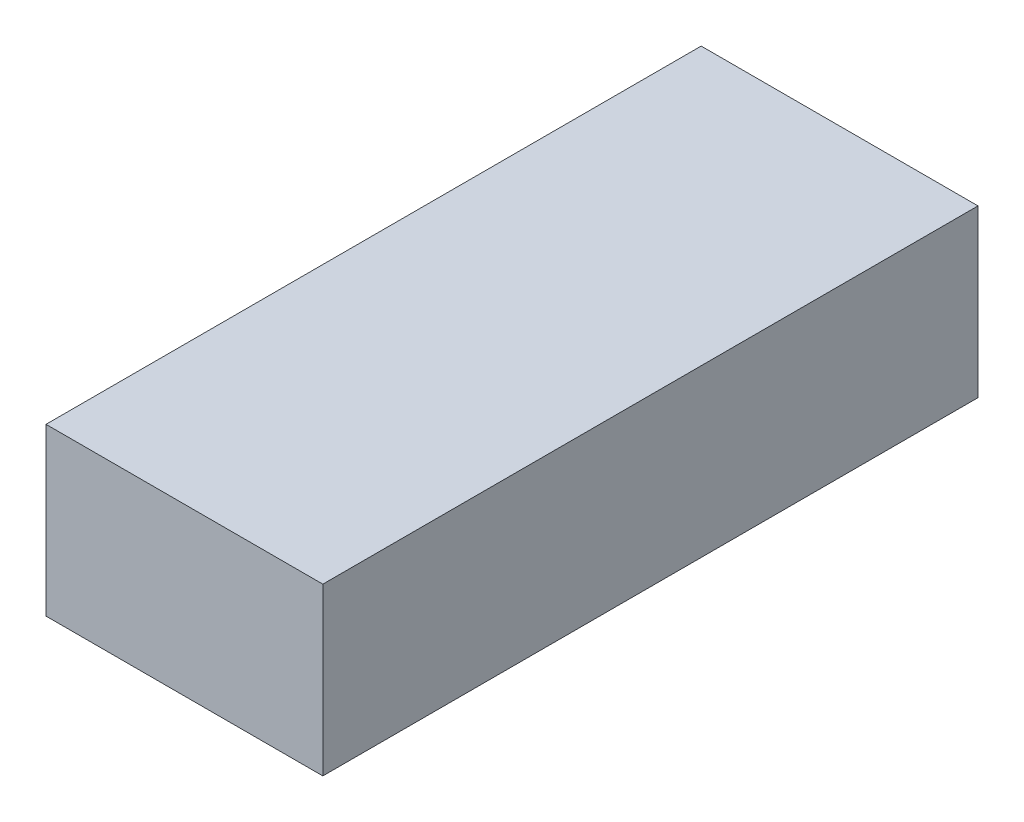
SolidWorks part; units mm, degrees
ref_plane "Front Plane" through (0, 0, 0) normal (0, 0, 1) x (1, 0, 0)
ref_plane "Top Plane" through (0, 0, 0) normal (0, 1, 0) x (1, 0, 0)
ref_plane "Right Plane" through (0, 0, 0) normal (1, 0, 0) x (0, 0, -1)
sketch "Sketch1" plane through (0, 0, 0) normal (0, 1, 0) x (1, 0, 0)
  line L1 (-15, 35.5) -> (15, 35.5)
  line L2 (-15, 35.5) -> (-15, -35.5)
  line L3 (-15, -35.5) -> (15, -35.5)
  line L4 (15, 35.5) -> (15, -35.5)
  line L5 (-15, 35.5) -> (15, -35.5) construction
  line L6 (-15, -35.5) -> (15, 35.5) construction
  point P0 (0, 0)
  dimension "D1" = 30
  dimension "D2" = 71
extrude "Boss-Extrude1" add sketch "Sketch1" along normal blind 18
